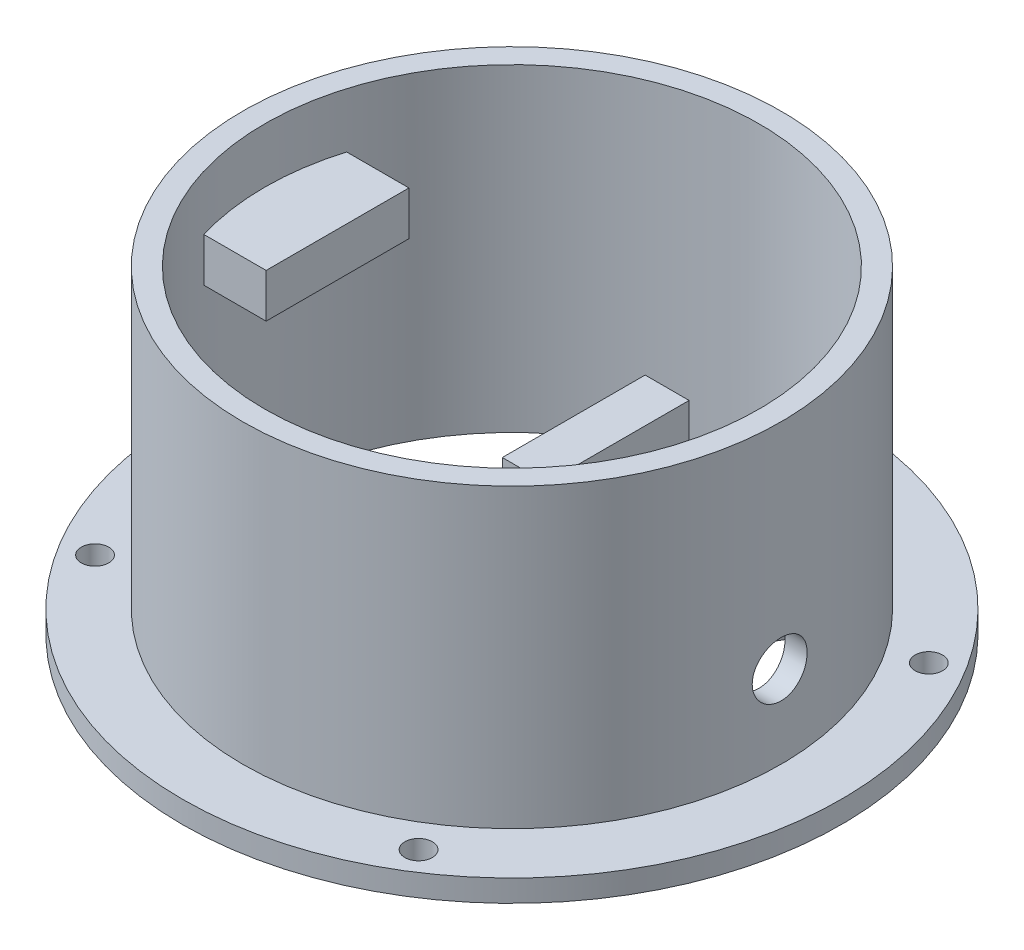
SolidWorks part; units mm, degrees
ref_plane "Front Plane" through (0, 0, 0) normal (0, 0, 1) x (1, 0, 0)
ref_plane "Top Plane" through (0, 0, 0) normal (0, 1, 0) x (1, 0, 0)
ref_plane "Right Plane" through (0, 0, 0) normal (1, 0, 0) x (0, 0, -1)
sketch "Sketch1" plane through (0, 0, 0) normal (0, 1, 0) x (1, 0, 0)
  circle A0 centre (0, 0) radius 45
  circle A1 centre (0, 0) radius 60
  dimension "D1" = 90
  dimension "D2" = 120
extrude "Boss-Extrude3" add sketch "Sketch1" along normal blind 4
sketch "Sketch9" plane through (0, 4, 0) normal (0, 1, 0) x (1, 0, 0)
  circle A0 centre (0, 0) radius 45 construction
  circle A1 centre (0, 0) radius 45
  circle A2 centre (0, 0) radius 49
  dimension "D1" = 4
extrude "Boss-Extrude5" add sketch "Sketch9" along normal blind 54
sketch "Sketch10" plane through (0, 0, 0) normal (0, 0, 1) x (1, 0, 0)
  line L0 (0, 58) -> (0, 0) construction
  line L1 (49, 58) -> (-49, 58) construction
  line L2 (45, 58) -> (-45, 58) construction
  line L3 (11.25, 0) -> (19.25, 0)
  line L4 (11.25, 0) -> (11.25, 40)
  line L5 (11.25, 40) -> (19.25, 40)
  line L6 (19.25, 0) -> (19.25, 40)
  line L7 (-49, 58) -> (-49, 4) construction
  line L8 (-46.75, 48) -> (-31.75, 48)
  line L9 (-46.75, 48) -> (-46.75, 40)
  line L10 (-46.75, 40) -> (-31.75, 40)
  line L11 (-31.75, 48) -> (-31.75, 40)
  dimension "D1" = 8
  dimension "D2" = 11.25
  dimension "D3" = 18
  dimension "D4" = 18
  dimension "D5" = 2.25
  dimension "D6" = 15
  dimension "D7" = 8
extrude "Boss-Extrude6" add sketch "Sketch10" along normal mid plane 26
sketch "Sketch12" plane through (11.25, 0, 0) normal (-1, 0, 0) x (0, 0, 1)
  line L0 (0, 40) -> (0, 0) construction
  line L1 (13, 40) -> (-13, 40) construction
  line L2 (13, 0) -> (-13, 0) construction
  line L3 (-5, 5) -> (5, 5)
  line L4 (-5, 5) -> (-5, 30)
  line L5 (-5, 30) -> (5, 30)
  line L6 (5, 5) -> (5, 30)
  line L7 (-5, 5) -> (5, 30) construction
  line L8 (-5, 30) -> (5, 5) construction
  point P5 (0, 17.5)
  dimension "D1" = 5
  dimension "D2" = 10
  dimension "D3" = 10
extrude "Cut-Extrude1" cut sketch "Sketch12" against normal up to surface (8 mm away) up to face at (19.25, 20, 0)
sketch "Sketch13" plane through (11.25, 0, 0) normal (-1, 0, 0) x (0, 0, 1)
  line L0 (0, 30) -> (0, 5) construction
  line L1 (5, 30) -> (-5, 30) construction
  line L2 (-5, 5) -> (5, 5) construction
  circle A0 centre (0, 19) radius 5
  dimension "D2" = 10
  dimension "D1" = 14
extrude "Cut-Extrude2" cut sketch "Sketch13" against normal through all
sketch "Sketch14" plane through (0, 0, 0) normal (0, -1, 0) x (1, 0, 0)
  line L0 (-34, 13) -> (-34, -13) construction
  line L1 (-43.0813, 13) -> (-31.75, 13) construction
  line L2 (-43.0813, -13) -> (-31.75, -13) construction
  line L3 (-34, 0) -> (14, 0) construction
  line L4 (14, -13) -> (14, 13) construction
  line L5 (11.25, 13) -> (19.25, 13) construction
  circle A0 centre (-34, -7.7978) radius 1.4
  circle A1 centre (14, -7.7978) radius 1.4
  circle A2 centre (14, 7.7978) radius 1.4
  circle A3 centre (-34, 7.7978) radius 1.4
  point P15 (14, 0)
  dimension "D3" = 2.8
  dimension "D1" = 2.25
  dimension "D2" = 48
extrude "Cut-Extrude3" cut sketch "Sketch14" against normal blind 7.2
sketch "Sketch15" plane through (0, 0, 0) normal (0, -1, 0) x (1, 0, 0)
  line L2 (11.25, 13) -> (11.25, -13)
  line L3 (11.25, -13) -> (25.2498, -37.2484)
  line L4 (11.25, 13) -> (25.2498, 37.2484)
  line L5 (24.25, 21.5167) -> (27.1673, 26.5695)
  line L6 (24.25, -21.5167) -> (27.1673, -26.5695)
  line L7 (24.25, 21.5167) -> (24.25, -21.5167)
  line L8 (19.25, 13) -> (19.25, -13) construction
  line L9 (17.3122, 9.5) -> (27.1673, 26.5695) construction
  line L10 (17.3122, -9.5) -> (27.1673, -26.5695) construction
  circle A0 centre (0, 0) radius 45 construction
  arc A1 (25.2498, -37.2484) -> (25.2498, 37.2484) centre (0, 0) ccw
  arc A2 (25.2498, -37.2484) -> (-16.8833, -35.7284) centre (5.6167, 3.2428) cw
  arc A3 (27.1673, -26.5695) -> (27.1673, 26.5695) centre (0, 0) ccw
  circle M4 centre (0, 0) radius 45
  dimension "D2" = 7
  dimension "D3" = 5
sketch "Sketch16" plane through (0, 0, 0) normal (0, -1, 0) x (1, 0, 0)
extrude "Boss-Extrude10" add sketch "Sketch15" against normal blind 4 contours L4 L2 L3 A3 L6 L7 L5 M4
sketch "Sketch18" plane through (0, 4, 0) normal (0, 1, 0) x (1, 0, 0)
  circle A0 centre (0, 0) radius 55 construction
  circle A1 centre (46.4514, 29.4494) radius 2.5
  circle A2 centre (29.4494, -46.4514) radius 2.5
  circle A3 centre (-46.4514, -29.4494) radius 2.5
  circle A4 centre (-29.4494, 46.4514) radius 2.5
  dimension "D1" = 5
  dimension "D2" = 110
  dimension "D3" = 4
extrude "Cut-Extrude4" cut sketch "Sketch18" against normal through all
